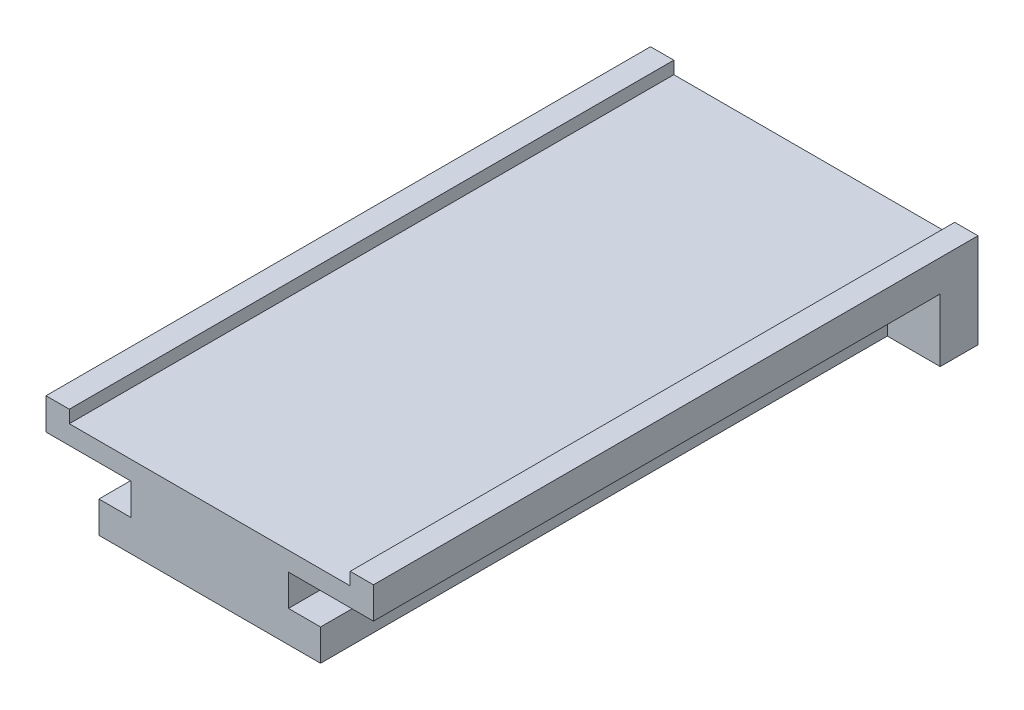
SolidWorks part; units mm, degrees
ref_plane "Front Plane" through (0, 0, 0) normal (0, 0, 1) x (1, 0, 0)
ref_plane "Top Plane" through (0, 0, 0) normal (0, 1, 0) x (1, 0, 0)
ref_plane "Right Plane" through (0, 0, 0) normal (1, 0, 0) x (0, 0, -1)
sketch "Sketch1" plane through (0, 0, 0) normal (0, 0, 1) x (1, 0, 0)
  line L1 (-3.2029, -2.2101) -> (5.5971, -2.2101)
  line L2 (-3.2029, -2.2101) -> (-3.2029, -4.7101)
  line L3 (-3.2029, -4.7101) -> (5.5971, -4.7101)
  line L4 (5.5971, -2.2101) -> (5.5971, -4.7101)
  line L5 (-3.2029, 0.2899) -> (3.0471, 0.2899)
  line L6 (-3.2029, 0.2899) -> (-3.2029, -2.2101)
  line L7 (-3.2029, -2.2101) -> (3.0471, -2.2101)
  line L8 (3.0471, 0.2899) -> (3.0471, -2.2101)
  line L13 (-3.2029, 0.2899) -> (9.7971, 0.2899)
  line L14 (-3.2029, 0.2899) -> (-3.2029, 2.7899)
  line L15 (-3.2029, 2.7899) -> (9.7971, 2.7899)
  line L16 (9.7971, 0.2899) -> (9.7971, 2.7899)
  dimension "D1" = 2.5
  dimension "D2" = 2.5
  dimension "D3" = 2.5
  dimension "D4" = 8.8
  dimension "D5" = 6.25
  dimension "D6" = 13
extrude "Boss-Extrude1" add sketch "Sketch1" along normal blind 45 contours L13 L16 L15 L14 L5 | L8 L5 L6 L1 | L4 L1 L2 L3
sketch "Sketch2" plane through (9.7971, 0, 0) normal (1, 0, 0) x (0, 0, -1)
  line L1 (-45, -4.7101) -> (-36.3578, -4.7101)
  line L2 (-45, -4.7101) -> (-45, -7.7101)
  line L3 (-45, -7.7101) -> (-36.3578, -7.7101)
  line L4 (-36.3578, -4.7101) -> (-36.3578, -7.7101)
  line L5 (-45, -7.7101) -> (-43, -7.7101)
  line L6 (-45, -7.7101) -> (-45, -14.7101)
  line L7 (-45, -14.7101) -> (-43, -14.7101)
  line L8 (-43, -7.7101) -> (-43, -14.7101)
  dimension "D1" = 3
  dimension "D2" = 7
  dimension "D3" = 2
mirror "Mirror1" about plane through (-3.2029, 0, 45) normal (-1, 0, 0) of "Boss-Extrude1"
sketch "Sketch8" plane through (0, -4.7101, 0) normal (0, -1, 0) x (1, 0, 0)
  line L0 (-3.2029, 45) -> (-3.2029, -0.3624) construction
  line L1 (-12.0029, 45) -> (5.5971, 45) construction
  line L2 (-16.2029, 45) -> (-16.2029, 0) construction
  line L3 (-16.2029, 22.5) -> (9.7971, 22.5) construction
  line L4 (9.7971, 45) -> (9.7971, 0) construction
  circle A0 centre (-3.2029, 32.5) radius 1.5
  circle A1 centre (-3.2029, 12.5) radius 1.5
  dimension "D1" = 10
extrude "Cut-Extrude2" cut sketch "Sketch8" against normal blind 3 draft 45
sketch "Sketch9" plane through (0, 0, 0) normal (0, 0, -1) x (-1, 0, 0)
  line L0 (12.0029, -4.7101) -> (-5.5971, -4.7101) construction
  line L1 (-9.7971, 2.7899) -> (16.2029, 2.7899)
  line L2 (-9.7971, 2.7899) -> (-9.7971, -4.7101)
  line L3 (-9.7971, -4.7101) -> (16.2029, -4.7101)
  line L4 (16.2029, 2.7899) -> (16.2029, -4.7101)
extrude "Boss-Extrude3" add sketch "Sketch9" along normal blind 3
sketch "Sketch10" plane through (0, 2.7899, 0) normal (0, 1, 0) x (1, 0, 0)
  line L0 (-3.2029, 3) -> (-3.2029, -45) construction
  line L1 (-16.2029, 3) -> (9.7971, 3) construction
  line L2 (-16.2029, -45) -> (9.7971, -45) construction
  line L3 (-14.3529, 3) -> (-14.3529, -45)
  line L4 (-14.3529, 3) -> (7.9471, 3)
  line L5 (-3.2029, 3) -> (-3.2029, -45)
  line L6 (-14.3529, -45) -> (7.9471, -45)
  line L7 (7.9471, 3) -> (7.9471, -45)
  line M7 (9.7971, 3) -> (-16.2029, 3)
  line M9 (-16.2029, -45) -> (9.7971, -45)
  dimension "D1" = 11.15
extrude "Cut-Extrude3" cut sketch "Sketch10" against normal blind 1 contours L5 L4 L3 M9 | L7 L5 M7 M9
